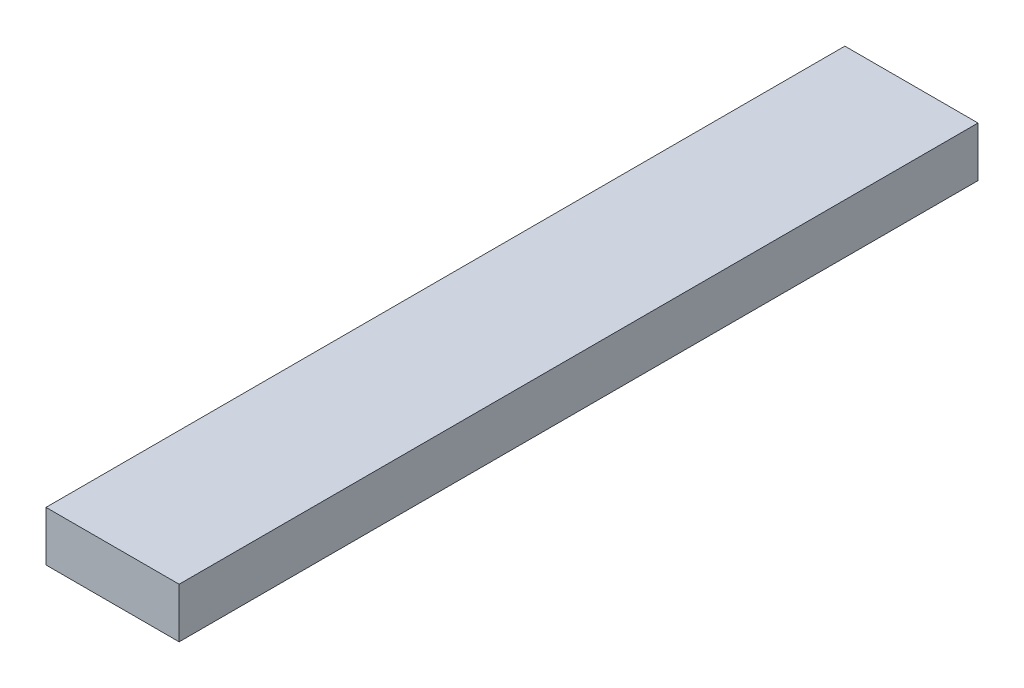
SolidWorks part; units mm, degrees
ref_plane "Front Plane" through (0, 0, 0) normal (0, 0, 1) x (1, 0, 0)
ref_plane "Top Plane" through (0, 0, 0) normal (0, 1, 0) x (1, 0, 0)
ref_plane "Right Plane" through (0, 0, 0) normal (1, 0, 0) x (0, 0, -1)
sketch "Sketch1" plane through (0, 0, 0) normal (0, 0, 1) x (1, 0, 0)
  line L0 (0, 4.7625) -> (0, -4.7625)
  line L1 (-12.7, 0) -> (12.7, 0) construction
  point P6 (0, 0)
  dimension "Width" = 25.4
  dimension "Thk" = 9.525
sketch "Sketch2" plane through (0, 0, 0) normal (1, 0, 0) x (0, 0, -1)
  line L0 (76.2, 0) -> (-76.2, 0)
  point P4 (0, 0)
  dimension "Length" = 152.4
sketch "Sketch3" plane through (0, 0, 0) normal (0, 0, 1) x (1, 0, 0)
  line L1 (12.7, 4.7625) -> (-12.7, 4.7625)
  line L2 (12.7, 4.7625) -> (12.7, -4.7625)
  line L3 (12.7, -4.7625) -> (-12.7, -4.7625)
  line L4 (-12.7, 4.7625) -> (-12.7, -4.7625)
  line L5 (12.7, 4.7625) -> (-12.7, -4.7625) construction
  line L6 (12.7, -4.7625) -> (-12.7, 4.7625) construction
  point P0 (0, 0)
extrude "Boss-Extrude1" add sketch "Sketch3" along normal up to vertex (76.2 mm away) and the other way up to vertex (76.2 mm away) up to point (0, 0, 76.2) other way up to point (0, 0, -76.2)
